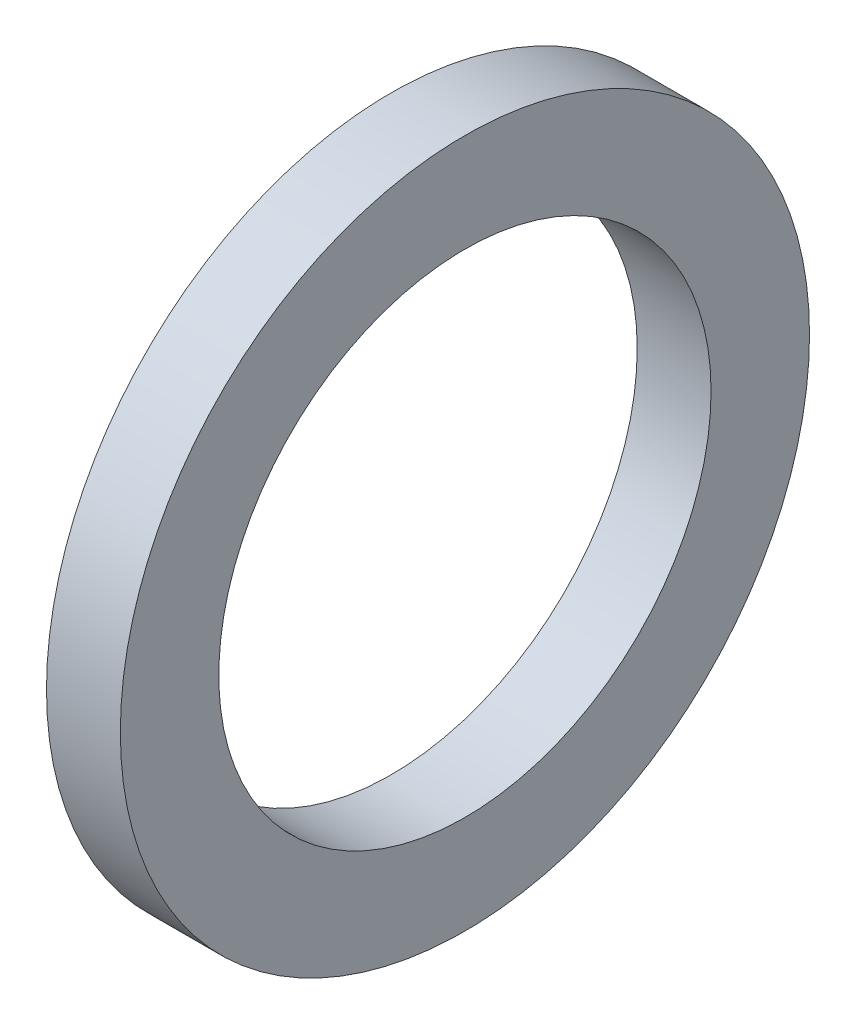
SolidWorks part; units mm, degrees
material "SUS304"
ref_plane "Front Plane" through (0, 0, 0) normal (0, 0, 1) x (1, 0, 0)
ref_plane "Top Plane" through (0, 0, 0) normal (0, 1, 0) x (1, 0, 0)
ref_plane "Right Plane" through (0, 0, 0) normal (1, 0, 0) x (0, 0, -1)
sketch "Sketch1" plane through (0, 0, 0) normal (1, 0, 0) x (0, 0, -1)
  circle A0 centre (0, 0) radius 10
  circle A1 centre (0, 0) radius 14
  dimension "D1" = 20
  dimension "D2" = 28
extrude "Boss-Extrude1" add sketch "Sketch1" along normal blind 3
equation "\"Mass Kg\"= \"SW-Mass\""
